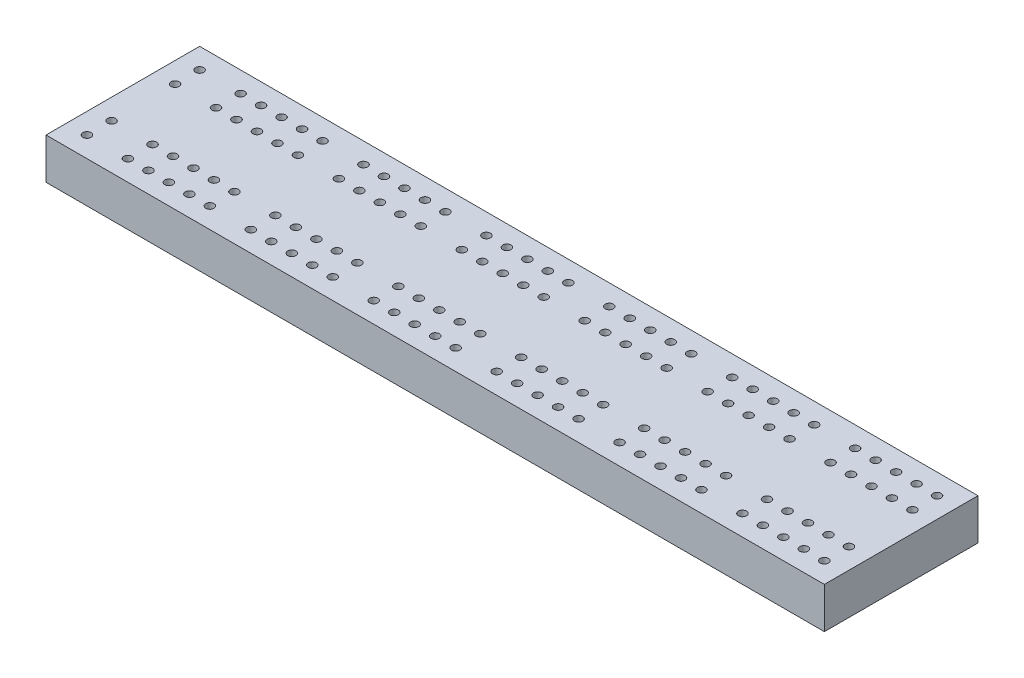
SolidWorks part; units mm, degrees
ref_plane "Front Plane" through (0, 0, 0) normal (0, 0, 1) x (1, 0, 0)
ref_plane "Top Plane" through (0, 0, 0) normal (0, 1, 0) x (1, 0, 0)
ref_plane "Right Plane" through (0, 0, 0) normal (1, 0, 0) x (0, 0, -1)
sketch "Sketch1" plane through (0, 0, 0) normal (0, 1, 0) x (1, 0, 0)
  line L0 (0, 0) -> (378.5552, 0) construction
  line L1 (0, -37.5) -> (380, -37.5)
  line L2 (0, -37.5) -> (0, 37.5)
  line L3 (0, 37.5) -> (380, 37.5)
  line L4 (380, -37.5) -> (380, 37.5)
  point P7 (0, 0)
  dimension "D1" = 75
  dimension "D2" = 380
extrude "Boss-Extrude1" add sketch "Sketch1" along normal mid plane 20
sketch "Sketch6" plane through (0, 10, 0) normal (0, 1, 0) x (1, 0, 0)
  line L0 (0, 37.5) -> (0, -37.5) construction
  line L1 (380, 37.5) -> (0, 37.5) construction
  point P0 (10, 27.5)
  dimension "D1" = 10
  dimension "D2" = 10
hole_wizard "Ø4.0 (4) Diameter Hole1" positions "Sketch6" profile "Sketch7" hole size "Ø4.0" standard "ANSI Metric"
sketch "Sketch7" plane through (10, 10, -27.5) normal (1, 0, 0) x (0, 0, 1)
  line L0 (0, 0) -> (0, 13.2017)
  line L1 (0, 13.2017) -> (2, 12)
  line L2 (2, 12) -> (2, 0)
  line L5 (2, 0) -> (0, 0)
  line L10 (0, 13.2017) -> (-2, 12) construction
  line L11 (0, -6.35) -> (0, 107.95) construction
  dimension "Hole Dia." = 4
  dimension "Hole Depth" = 12
  dimension "Drill Angle" = 118
pattern_linear "LPattern1" count 2 spacing 12 along (0, 0, 1) count 38 spacing 10 along (1, 0, 0) skipping (0, 1), (0, 7), (0, 13), (0, 19), (0, 25), (0, 31), (0, 37), (1, 1), (1, 7), (1, 13), (1, 19), (1, 25), (1, 31), (1, 37) of "Ø4.0 (4) Diameter Hole1"
mirror "Mirror1" about plane through (0, 0, 0) normal (0, 0, 1) of "LPattern1", "Ø4.0 (4) Diameter Hole1"
